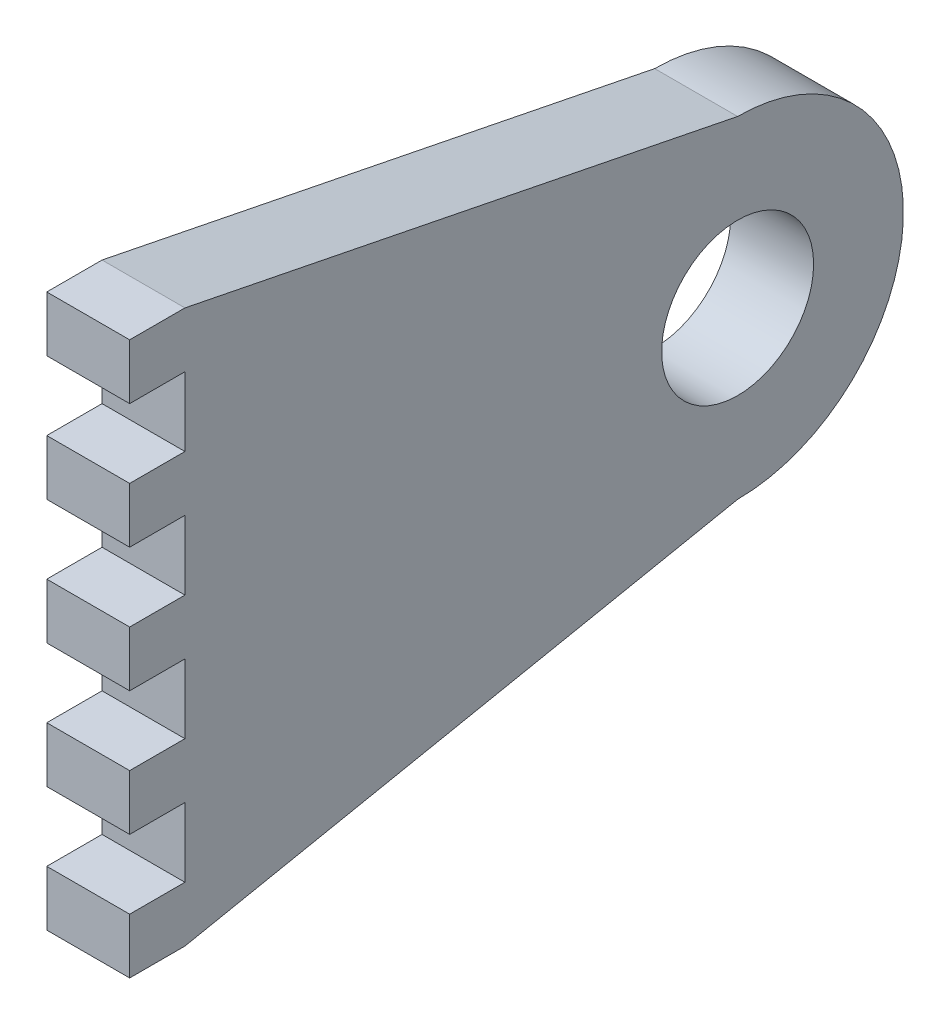
SolidWorks part; units mm, degrees
ref_plane "Front Plane" through (0, 0, 0) normal (0, 0, 1) x (1, 0, 0)
ref_plane "Top Plane" through (0, 0, 0) normal (0, 1, 0) x (1, 0, 0)
ref_plane "Right Plane" through (0, 0, 0) normal (1, 0, 0) x (0, 0, -1)
sketch "Sketch1" plane through (0, 0, 0) normal (1, 0, 0) x (0, 0, -1)
  line L0 (-20, 5.5) -> (-22, 5.5)
  line L1 (-20, 8) -> (-20, 5.5)
  line L2 (-20, 3.5) -> (-20, 1)
  line L3 (-20, -1) -> (-20, -3.5)
  line L4 (-20, -5.5) -> (-20, -8)
  line L5 (0, -6) -> (-20, -10)
  line L6 (-22, 1) -> (-20, 1)
  line L7 (-20, -3.5) -> (-22, -3.5)
  line L8 (-20, -8) -> (-22, -8)
  line L10 (-20, 3.5) -> (-22, 3.5)
  line L11 (-20, -1) -> (-22, -1)
  line L12 (-20, -5.5) -> (-22, -5.5)
  line L13 (-20, -10) -> (-22, -10)
  line L14 (-22, 5.5) -> (-22, 3.5)
  line L15 (-22, 1) -> (-22, -1)
  line L16 (-22, -3.5) -> (-22, -5.5)
  line L17 (-22, -8) -> (-22, -10)
  line L18 (-22, 10) -> (-22, 8)
  line L19 (-20, 8) -> (-22, 8)
  line L22 (-22, 10) -> (-20, 10)
  line L23 (0, 6) -> (-20, 10)
  line L25 (0, 0) -> (-20, 0) construction
  circle A0 centre (0, 0) radius 2.75
  arc A1 (0, -6) -> (0, 6) centre (0, 0) ccw
  point P16 (-20, 0)
  point P17 (-22, 0)
  point P18 (0, 0)
  dimension "D1" = 5.5
  dimension "D2" = 2.5
  dimension "D5" = 2
  dimension "D9" = 12
  dimension "D3" = 0
  dimension "D7" = 4
  dimension "2.5" = 2.5
  dimension "D4" = 2
extrude "Boss-Extrude1" add sketch "Sketch1" along normal blind 3
